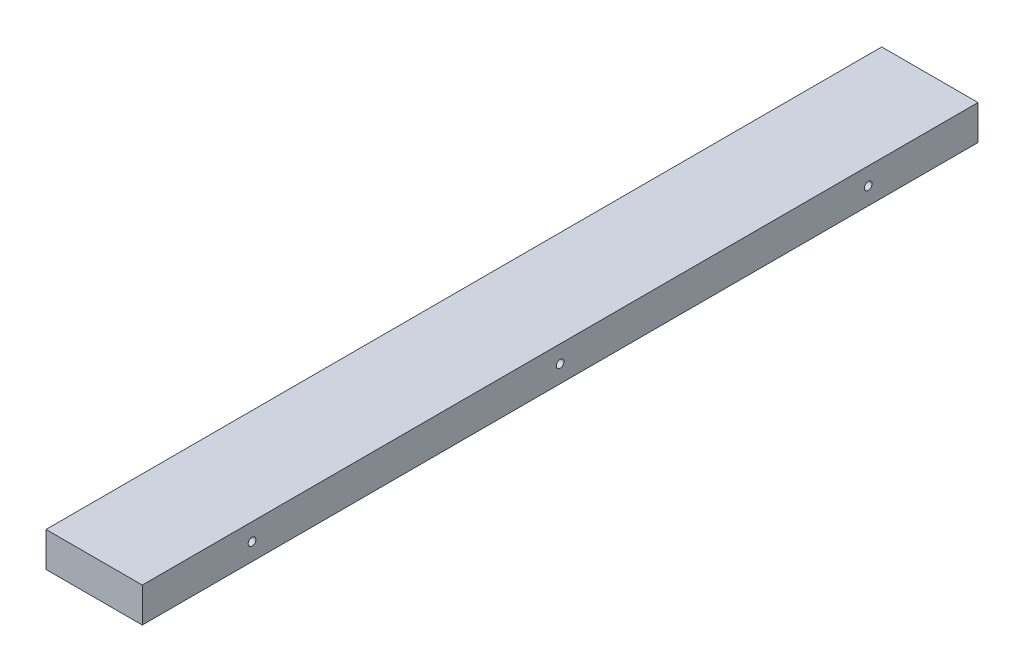
SolidWorks part; units mm, degrees
ref_plane "Front Plane" through (0, 0, 0) normal (0, 0, 1) x (1, 0, 0)
ref_plane "Top Plane" through (0, 0, 0) normal (0, 1, 0) x (1, 0, 0)
ref_plane "Right Plane" through (0, 0, 0) normal (1, 0, 0) x (0, 0, -1)
sketch "Sketch1" plane through (0, 0, 0) normal (0, 1, 0) x (1, 0, 0)
  line L1 (-25, 217) -> (25, 217)
  line L2 (-25, 217) -> (-25, -217)
  line L3 (-25, -217) -> (25, -217)
  line L4 (25, 217) -> (25, -217)
  line L5 (-25, 217) -> (25, -217) construction
  line L6 (-25, -217) -> (25, 217) construction
  point P0 (0, 0)
  dimension "D1" = 434
  dimension "D2" = 50
extrude "Boss-Extrude1" add sketch "Sketch1" along normal blind 18
hole_wizard "Ø4.0 (4) Diameter Hole3" positions "Sketch7" profile "Sketch6" hole size "Ø4.0" standard "ISO"
sketch "Sketch7" plane through (25, 0, 0) normal (1, 0, 0) x (0, 0, -1)
  point P0 (160, 9)
  point P3 (0, 9)
  point P6 (-160, 9)
sketch "Sketch6" plane through (25, 9, -160) normal (0, 1, 0) x (0, 0, -1)
  line L0 (0, 0) -> (0, 31.2017)
  line L1 (0, 31.2017) -> (2, 30)
  line L2 (2, 30) -> (2, 0)
  line L5 (2, 0) -> (0, 0)
  line L10 (0, 31.2017) -> (-2, 30) construction
  line L11 (0, -6.35) -> (0, 107.95) construction
  dimension "Hole Dia." = 4
  dimension "Hole Depth" = 30
  dimension "Drill Angle" = 118
hole_wizard "Ø4.0 (4) Diameter Hole4" positions "Sketch9" profile "Sketch8" hole size "Ø4.0" standard "ISO"
sketch "Sketch9" plane through (-25, 0, 0) normal (-1, 0, 0) x (0, 0, 1)
  point P4 (180, 9)
  point P7 (60, 9)
  point P10 (-60, 9)
  point P13 (-180, 9)
sketch "Sketch8" plane through (-25, 9, 180) normal (0, 1, 0) x (0, 0, 1)
  line L0 (0, 0) -> (0, 31.2017)
  line L1 (0, 31.2017) -> (2, 30)
  line L2 (2, 30) -> (2, 0)
  line L5 (2, 0) -> (0, 0)
  line L10 (0, 31.2017) -> (-2, 30) construction
  line L11 (0, -6.35) -> (0, 107.95) construction
  dimension "Hole Dia." = 4
  dimension "Hole Depth" = 30
  dimension "Drill Angle" = 118
